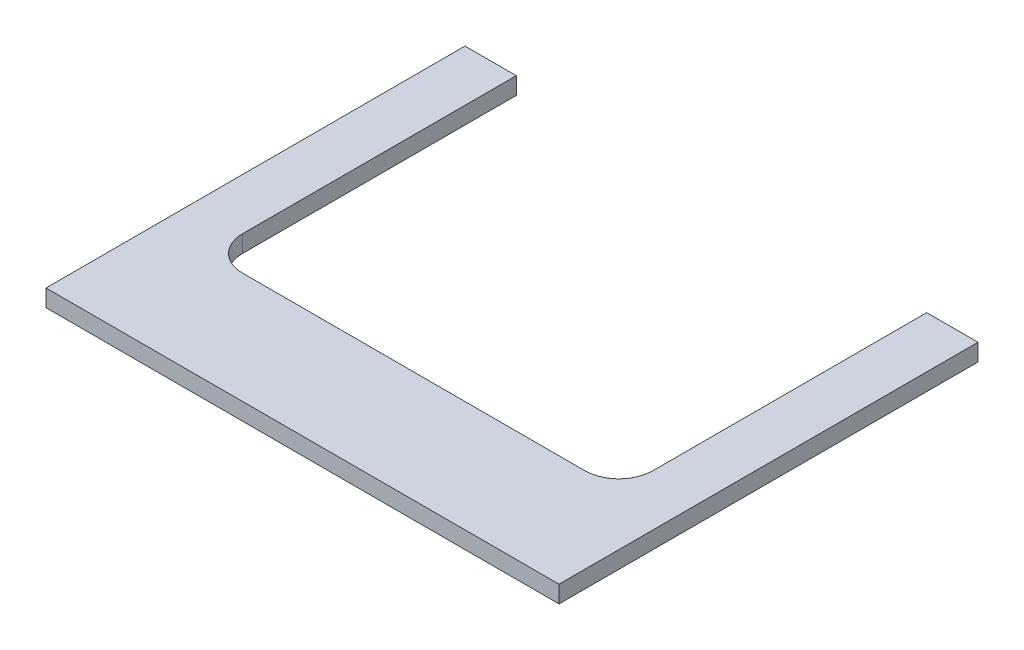
SolidWorks part; units mm, degrees
ref_plane "前视基准面" through (0, 0, 0) normal (0, 0, 1) x (1, 0, 0)
ref_plane "上视基准面" through (0, 0, 0) normal (0, 1, 0) x (1, 0, 0)
ref_plane "右视基准面" through (0, 0, 0) normal (1, 0, 0) x (0, 0, -1)
sketch "草图1" plane through (0, 0, 0) normal (0, 1, 0) x (1, 0, 0)
  line L1 (-120, 32.5) -> (120, 32.5)
  line L2 (-150, 212.5) -> (-120, 212.5)
  line L3 (-150, 212.5) -> (-150, 32.5)
  line L5 (-150, 32.5) -> (150, -32.5) construction
  line L6 (-150, -32.5) -> (150, 32.5) construction
  line L7 (-150, 32.5) -> (-150, -32.5)
  line L8 (-120, 212.5) -> (-120, 32.5)
  line L9 (150, 32.5) -> (150, 212.5)
  line L10 (150, 212.5) -> (120, 212.5)
  line L11 (-150, -32.5) -> (150, -32.5)
  line L12 (150, 32.5) -> (150, -32.5)
  line L13 (120, 32.5) -> (120, 212.5)
  point P0 (0, 0)
  dimension "D1" = 300
  dimension "D2" = 240
  dimension "D3" = 180
  dimension "D4" = 65
extrude "凸台-拉伸1" add sketch "草图1" along normal blind 10
fillet "圆角7" radius 20 2 edges at (120, 5, -32.5) (-120, 5, -32.5)
